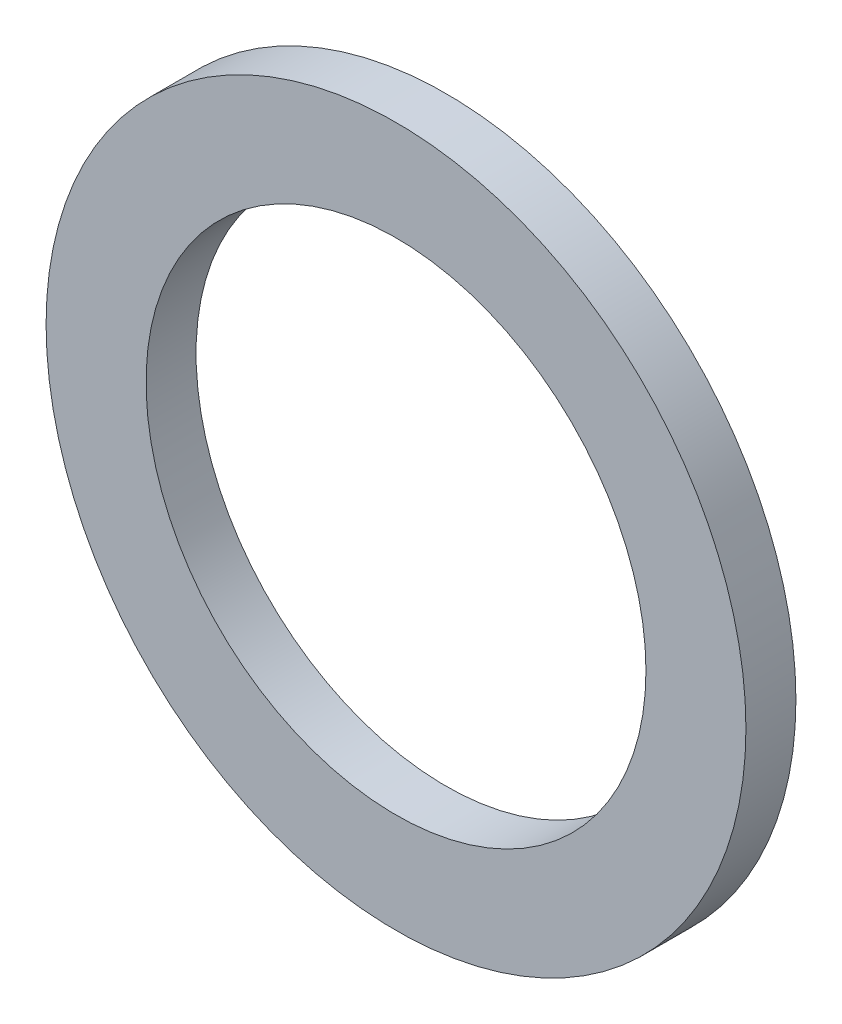
SolidWorks part; units mm, degrees
ref_plane "Front Plane" through (0, 0, 0) normal (0, 0, 1) x (1, 0, 0)
ref_plane "Top Plane" through (0, 0, 0) normal (0, 1, 0) x (1, 0, 0)
ref_plane "Right Plane" through (0, 0, 0) normal (1, 0, 0) x (0, 0, -1)
sketch "Sketch1" plane through (0, 0, 0) normal (0, 0, 1) x (1, 0, 0)
  circle A0 centre (0, 0) radius 2.5
  circle A1 centre (0, 0) radius 3.5
  dimension "D1" = 5
  dimension "D2" = 7
extrude "Boss-Extrude1" add sketch "Sketch1" along normal blind 0.5
